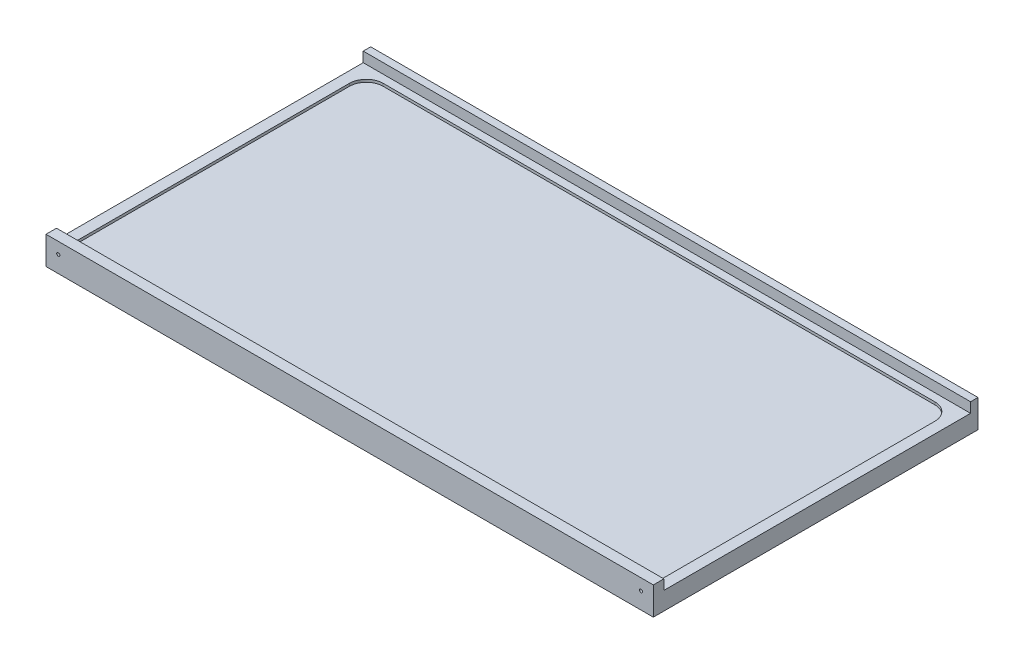
SolidWorks part; units mm, degrees
ref_plane "Front Plane" through (0, 0, 0) normal (0, 0, 1) x (1, 0, 0)
ref_plane "Top Plane" through (0, 0, 0) normal (0, 1, 0) x (1, 0, 0)
ref_plane "Right Plane" through (0, 0, 0) normal (1, 0, 0) x (0, 0, -1)
sketch "Sketch2" plane through (0, 0, 0) normal (0, 0, 1) x (1, 0, 0)
  line L1 (-954.25, 0) -> (954.25, 0)
  line L3 (-990, -50) -> (990, -50)
  line L5 (990, 8.5) -> (954.25, 8.5)
  line L6 (954.25, 8.5) -> (954.25, 0)
  line L7 (990, 8.5) -> (990, -50)
  line L9 (-990, 8.5) -> (-954.25, 8.5)
  line L10 (-954.25, 8.5) -> (-954.25, 0)
  line L11 (-990, -50) -> (-990, 8.5)
  line L12 (0, -50) -> (0, 0) construction
  dimension "D3" = 8.5
  dimension "D2" = 50
  dimension "D1" = 1980
  dimension "D4" = 35.75
extrude "Boss-Extrude1" add sketch "Sketch2" along normal mid plane 958.5
sketch "Sketch3" plane through (0, 0, 0) normal (0, 1, 0) x (1, 0, 0)
  line L0 (-990, 529.25) -> (990, 529.25)
  line L3 (990, 529.25) -> (990, 479.25)
  line L4 (990, 479.25) -> (-990, 479.25)
  line L6 (-990, 479.25) -> (-990, 529.25)
  line L8 (-990, -479.25) -> (-990, 479.25) construction
  line L9 (990, -479.25) -> (990, 479.25) construction
  dimension "D1" = 50
extrude "Boss-Extrude2" add sketch "Sketch3" along normal up to surface (58.5 mm away) from surface at -50 up to face at (-972.125, 8.5, 0) starting at face at (0, -50, 0)
fillet "Fillet1" radius 55 2 edges at (954.25, 4.25, -479.25) (-954.25, 4.25, -479.25)
sketch "Sketch4" plane through (0, 0, 0) normal (0, 1, 0) x (1, 0, 0)
  line L0 (-990, -479.25) -> (-990, 529.25) construction
  line L1 (990, -479.25) -> (-990, -479.25)
  line L2 (990, -479.25) -> (990, -529.25)
  line L3 (990, -529.25) -> (-990, -529.25)
  line L4 (-990, -479.25) -> (-990, -529.25)
  dimension "D1" = 50
extrude "Boss-Extrude4" add sketch "Sketch4" along normal up to surface (58.5 mm away) from surface at -50 up to face at (0, 8.5, -97.1282) starting at face at (0, -50, -25)
sketch "Sketch7" plane through (0, 0, 0) normal (0, 0, 1) x (1, 0, 0)
  line L0 (0, 50) -> (0, -50) construction
  line L4 (-990, -50) -> (990, -50) construction
  circle A0 centre (-950, 4.25) radius 5.1
  circle A2 centre (950, 4.25) radius 5.1
  point P5 (0, 0)
  point P8 (0, 0)
  dimension "D2" = 10.2
  dimension "D1" = 950
  dimension "D3" = 4.25
extrude "Cut-Extrude1" cut sketch "Sketch7" against normal up to surface (50 mm away) from surface at 529.25 up to face at (0, 4.25, 479.25) starting at face at (0, -20.75, 529.25)
sketch "Sketch8" plane through (0, 0, 0) normal (0, 1, 0) x (1, 0, 0)
  line L0 (-990, -529.25) -> (-990, 529.25) construction
  line L1 (990, 529.25) -> (-990, 529.25)
  line L2 (990, 529.25) -> (990, 505)
  line L3 (990, 505) -> (-990, 505)
  line L4 (-990, 529.25) -> (-990, 505)
  line L6 (-990, -495) -> (-1000, -495) construction
  line L7 (990, -529.25) -> (-990, -529.25)
  line L8 (990, -529.25) -> (990, -495)
  line L9 (990, -495) -> (-990, -495)
  line L10 (-990, -529.25) -> (-990, -495)
  point P16 (0, 0)
  dimension "D1" = 1000
extrude "Boss-Extrude5" add sketch "Sketch8" along normal up to surface (32.7 mm away) from surface at 8.5 starting at face at (0, 8.5, 81.837)
equation "\"absorber_plate_width\" = 1000mm"
equation "\"absorber_plate_length\" = 2000mm"
equation "\"absorber_plate_thickness\" = 4mm"
equation "\"groove_depth\" = 10mm"
equation "\"frame_thickness\" = 60mm"
equation "\"insulation_thickness\" = 50mm"
equation "\"glass_thickness\" = 3mm"
equation "\"pipe_distances\" = 100mm"
equation "\"pipe_OD\" = 8.5mm"
equation "\"pipe_ID\" = 7.8mm"
equation "\"D2@Sketch2\"=\"insulation_thickness\""
equation "\"D1@Sketch2\"=\"absorber_plate_length\"-\"groove_depth\"*2"
equation "\"D4@Sketch2\"=\"pipe_distances\"/2-\"groove_depth\"-\"pipe_OD\"/2"
equation "\"pipe_straight_length\" = 850mm"
equation "\"D1@Boss-Extrude1\"=\"absorber_plate_width\"-\"pipe_distances\"/2+\"pipe_OD\""
equation "\"D1@Sketch4\"=\"insulation_thickness\""
equation "\"D1@Sketch7\"=(\"absorber_plate_length\"-\"pipe_distances\")/2"
equation "\"D2@Sketch7\"=\"pipe_OD\"*1.2"
equation "\"D3@Sketch7\"=\"pipe_OD\"/2"
equation "\"D1@Sketch3\"=\"insulation_thickness\""
equation "\"D3@Sketch2\"=\"pipe_OD\""
equation "\"D1@Sketch8\"=\"absorber_plate_width\""
